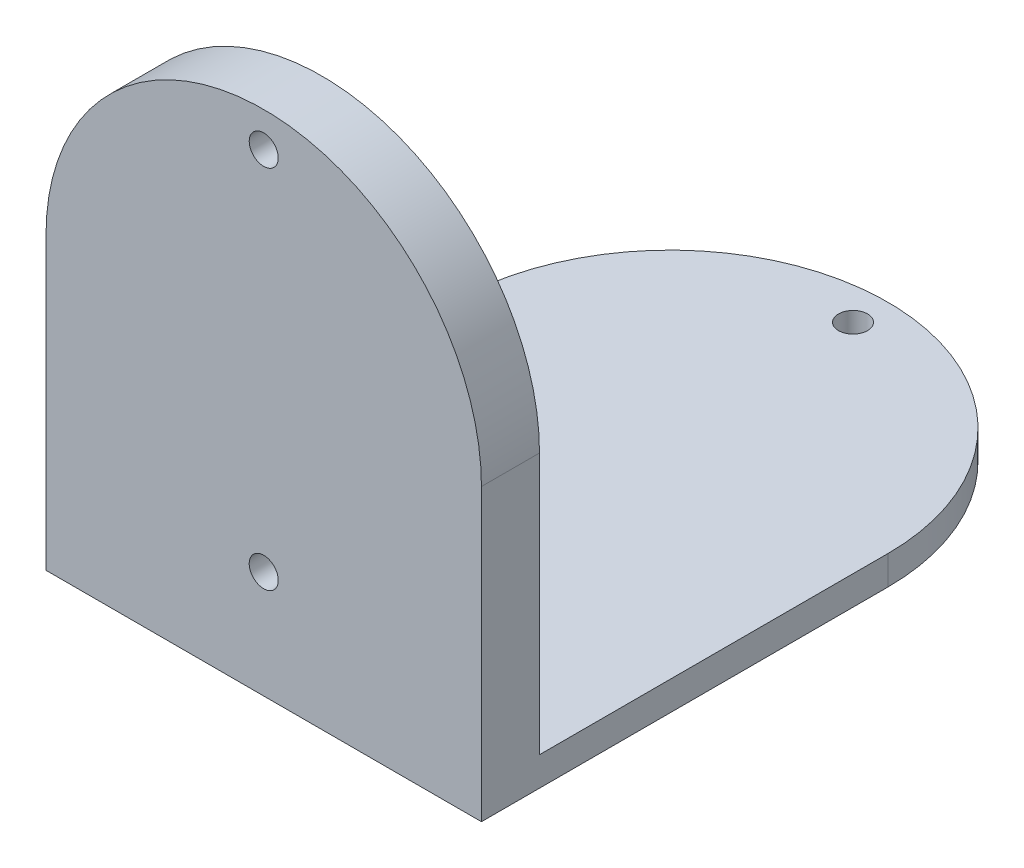
SolidWorks part; units mm, degrees
ref_plane "正面" through (0, 0, 0) normal (0, 0, 1) x (1, 0, 0)
ref_plane "平面" through (0, 0, 0) normal (0, 1, 0) x (1, 0, 0)
ref_plane "右側面" through (0, 0, 0) normal (1, 0, 0) x (0, 0, -1)
sketch "ｽｹｯﾁ1" plane through (0, 0, 0) normal (0, 1, 0) x (1, 0, 0)
  line L0 (-37.5, 0) -> (-37.5, -70)
  line L1 (-37.5, -70) -> (37.5, -70)
  line L2 (37.5, -70) -> (37.5, 0)
  circle A0 centre (0, 0) radius 37.5 construction
  arc A1 (-37.5, 0) -> (37.5, 0) centre (0, 0) cw
  dimension "D1" = 75
  dimension "D2" = 70
extrude "ﾎﾞｽ - 押し出し1" add sketch "ｽｹｯﾁ1" along normal blind 5
sketch "ｽｹｯﾁ18" plane through (0, 5, 0) normal (0, 1, 0) x (1, 0, 0)
  line L0 (37.5, -70) -> (37.5, 0) construction
  line L1 (-37.5, -70) -> (37.5, -70)
  line L2 (-37.5, -70) -> (-37.5, -60)
  line L3 (-37.5, -60) -> (37.5, -60)
  line L4 (37.5, -70) -> (37.5, -60)
  dimension "D1" = 10
extrude "ﾎﾞｽ - 押し出し2" add sketch "ｽｹｯﾁ18" along normal blind 30
sketch "ｽｹｯﾁ19" plane through (0, 5, 0) normal (0, 1, 0) x (1, 0, 0)
  line L0 (0, 0) -> (0, 31.5) construction
  line L1 (-37.5, 0) -> (37.5, 0) construction
  circle A0 centre (0, 31.5) radius 2.5
  circle A1 centre (0, -31.5) radius 2.5
  dimension "D1" = 31.5
  dimension "D2" = 5
extrude "ｶｯﾄ - 押し出し3" cut sketch "ｽｹｯﾁ19" against normal through all
sketch "ｽｹｯﾁ20" plane through (0, 0, 70) normal (0, 0, 1) x (1, 0, 0)
  line L0 (-37.5, 50) -> (-37.5, 35)
  line L1 (-37.5, 35) -> (37.5, 35)
  line L2 (37.5, 35) -> (37.5, 50)
  arc A0 (37.5, 50) -> (-37.5, 50) centre (0, 50) ccw
  point P1 (37.5, 55.5736)
  dimension "D1" = 75
  dimension "D2" = 50
extrude "ﾎﾞｽ - 押し出し3" add sketch "ｽｹｯﾁ20" against normal up to surface (10 mm away) up to face at (0, 20, 60)
sketch "ｽｹｯﾁ21" plane through (0, 0, 60) normal (0, 0, -1) x (-1, 0, 0)
  line L0 (0, 50) -> (0, 81.5) construction
  line L1 (-37.5, 50) -> (37.5, 50) construction
  circle A0 centre (0, 81.5) radius 2.5
  circle A1 centre (0, 18.5) radius 2.5
  dimension "D1" = 5
  dimension "D2" = 31.5
extrude "ｶｯﾄ - 押し出し4" cut sketch "ｽｹｯﾁ21" against normal through all
